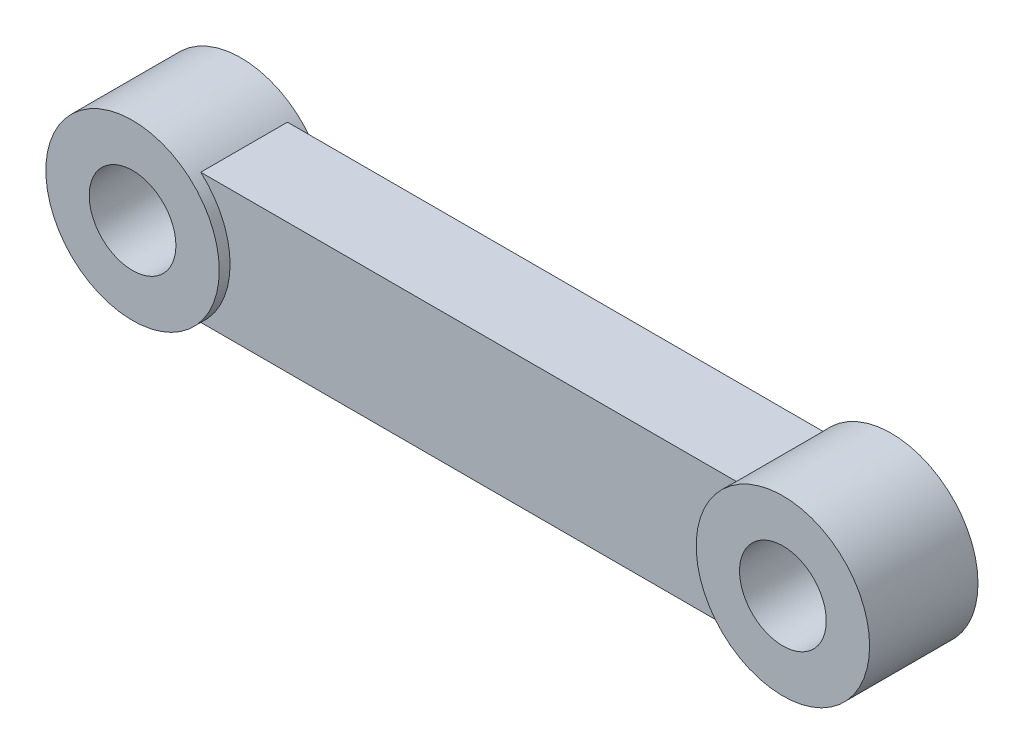
SolidWorks part; units mm, degrees
ref_plane "前视基准面" through (0, 0, 0) normal (0, 0, 1) x (1, 0, 0)
ref_plane "上视基准面" through (0, 0, 0) normal (0, 1, 0) x (1, 0, 0)
ref_plane "右视基准面" through (0, 0, 0) normal (1, 0, 0) x (0, 0, -1)
sketch "草图1" plane through (0, 0, 0) normal (0, 0, 1) x (1, 0, 0)
  circle A0 centre (0, 0) radius 8
  circle A1 centre (0, 0) radius 4
  circle A2 centre (60, 0) radius 8
  circle A3 centre (60, 0) radius 4
  dimension "D1" = 16
  dimension "D2" = 8
  dimension "D3" = 60
extrude "凸台-拉伸1" add sketch "草图1" along normal blind 10
ref_plane "基准面1" through (0, 0, 5) normal (0, 0, 1) x (1, 0, 0)
sketch "草图2" plane through (0, 0, 5) normal (0, 0, 1) x (1, 0, 0)
  line L0 (5.2915, 6) -> (54.7085, 6)
  line L1 (5.2915, -6) -> (54.7085, -6)
  line L2 (0, 0) -> (24.7807, 0) construction
  line L3 (5.2915, 6) -> (5.2915, -6)
  line L4 (54.7085, 6) -> (54.7085, -6)
  circle A0 centre (60, 0) radius 8 construction
  circle A1 centre (0, 0) radius 8 construction
  dimension "D1" = 12
extrude "凸台-拉伸2" add sketch "草图2" along normal mid plane 8
